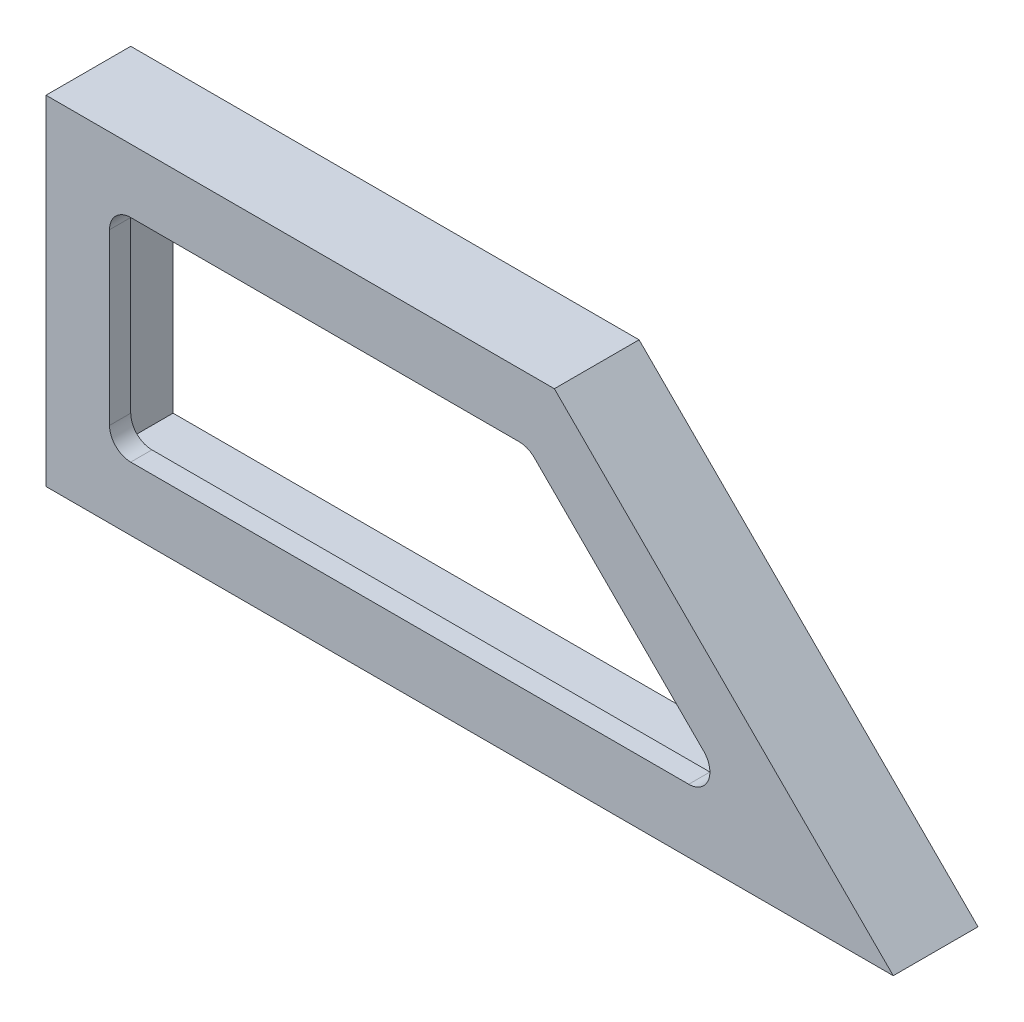
SolidWorks part; units mm, degrees
ref_plane "Front Plane" through (0, 0, 0) normal (0, 0, 1) x (1, 0, 0)
ref_plane "Top Plane" through (0, 0, 0) normal (0, 1, 0) x (1, 0, 0)
ref_plane "Right Plane" through (0, 0, 0) normal (1, 0, 0) x (0, 0, -1)
sketch "Sketch1" plane through (0, 0, 0) normal (0, 0, 1) x (1, 0, 0)
  line L0 (0, 8) -> (8, 0)
  line L1 (0, 0) -> (-12, 0)
  line L3 (0, 8) -> (-12, 8)
  line L4 (-12, 0) -> (-12, 8)
  line L5 (8, 0) -> (0, 0)
  dimension "D1" = 8
  dimension "D2" = 12
  dimension "D3" = 12
  dimension "D4" = 8
extrude "Boss-Extrude1" add sketch "Sketch1" along normal blind 2
sketch "Sketch2" plane through (0, 0, 2) normal (0, 0, 1) x (1, 0, 0)
  line L0 (-0.6213, 6.5) -> (4.3787, 1.5)
  line L1 (-10.5, 6.5) -> (-0.6213, 6.5)
  line L2 (-10.5, 6.5) -> (-10.5, 1.5)
  line L3 (-10.5, 1.5) -> (-0.6213, 1.5)
  line L5 (4.3787, 1.5) -> (-0.6213, 1.5)
  line L6 (0, 8) -> (-12, 8) construction
  line L7 (-12, 8) -> (-12, 0) construction
  line L8 (-12, 0) -> (8, 0) construction
  line L9 (8, 0) -> (0, 8) construction
  dimension "D1" = 1.5
  dimension "D2" = 1.5
  dimension "D3" = 1.5
  dimension "D4" = 1.5
  dimension "D5" = 1.5
extrude "Cut-Extrude1" cut sketch "Sketch2" against normal through all
sketch "Sketch3" plane through (0, 0, 0) normal (0, 0, -1) x (-1, 0, 0)
  line L0 (0.4142, 7) -> (-5.5858, 1)
  line L1 (11, 7) -> (0.4142, 7)
  line L2 (11, 7) -> (11, 1)
  line L3 (11, 1) -> (0.4142, 1)
  line L5 (-5.5858, 1) -> (0.4142, 1)
  line L6 (12, 0) -> (-8, 0) construction
  line L7 (12, 8) -> (12, 0) construction
  line L8 (0, 8) -> (12, 8) construction
  line L9 (-8, 0) -> (0, 8) construction
  dimension "D1" = 1
  dimension "D2" = 1
  dimension "D3" = 1
  dimension "D4" = 1
  dimension "D5" = 1
extrude "Cut-Extrude2" cut sketch "Sketch3" against normal blind 1.5
fillet "Fillet1" radius 0.5 4 edges at (-10.5, 1.5, 1.75) (4.3787, 1.5, 1.75) (-0.6213, 6.5, 1.75) (-10.5, 6.5, 1.75)
